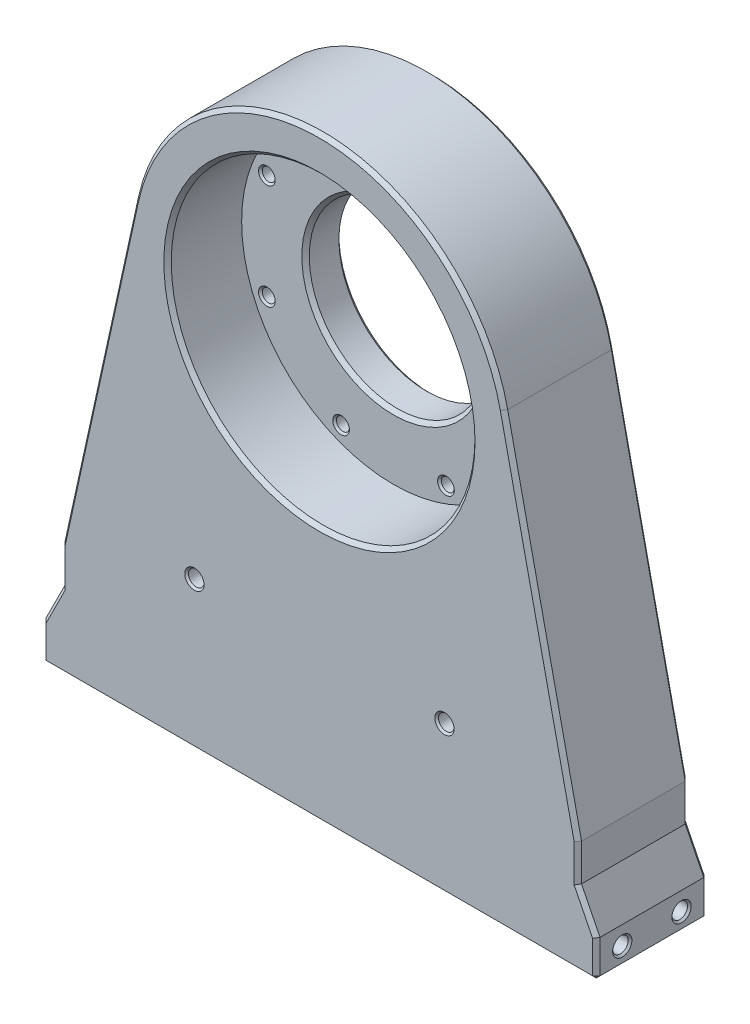
SolidWorks part; units mm, degrees
ref_plane "前视基准面" through (0, 0, 0) normal (0, 0, 1) x (1, 0, 0)
ref_plane "上视基准面" through (0, 0, 0) normal (0, 1, 0) x (1, 0, 0)
ref_plane "右视基准面" through (0, 0, 0) normal (1, 0, 0) x (0, 0, -1)
sketch "草图1" plane through (0, 0, 0) normal (0, 0, 1) x (1, 0, 0)
  line L1 (-74.75, 82.5) -> (74.75, 82.5)
  line L2 (-74.75, 82.5) -> (-74.75, -82.5)
  line L3 (-74.75, -82.5) -> (74.75, -82.5)
  line L4 (74.75, 82.5) -> (74.75, -82.5)
  line L5 (-74.75, 82.5) -> (74.75, -82.5) construction
  line L6 (-74.75, -82.5) -> (74.75, 82.5) construction
  point P0 (0, 0)
  dimension "D1" = 165
  dimension "D2" = 149.5
extrude "凸台-拉伸1" add sketch "草图1" along normal blind 30
sketch "草图2" plane through (0, 0, 30) normal (0, 0, 1) x (1, 0, 0)
  line L0 (-74.75, 82.5) -> (-74.75, -72.5)
  line L1 (-74.75, 82.5) -> (-74.75, -82.5) construction
  line L2 (-74.75, -72.5) -> (-69.75, -62.5)
  line L3 (-69.75, -62.5) -> (-69.75, 82.5)
  line L4 (74.75, 82.5) -> (-74.75, 82.5) construction
  line L5 (-69.75, 82.5) -> (-74.75, 82.5)
  line L6 (0, 82.5) -> (0, -82.5) construction
  line L7 (-74.75, -82.5) -> (74.75, -82.5) construction
  line L8 (69.75, 82.5) -> (74.75, 82.5)
  line L9 (69.75, -62.5) -> (69.75, 82.5)
  line L10 (74.75, -72.5) -> (69.75, -62.5)
  line L11 (74.75, 82.5) -> (74.75, -72.5)
  dimension "D1" = 5
  dimension "D2" = 10
  dimension "D3" = 10
extrude "切除-拉伸1" cut sketch "草图2" against normal through all
sketch "草图3" plane through (0, 0, 30) normal (0, 0, 1) x (1, 0, 0)
  line L0 (0, 82.5) -> (0, -82.5) construction
  line L1 (69.75, 82.5) -> (-69.75, 82.5) construction
  line L2 (-74.75, -82.5) -> (74.75, -82.5) construction
  circle A0 centre (0, 27.5) radius 41
  dimension "D1" = 82
  dimension "D2" = 55
extrude "切除-拉伸2" cut sketch "草图3" against normal offset from surface (20 mm away) 10 up to face at (0, -33.75, 0)
sketch "草图4" plane through (0, 0, 10) normal (0, 0, 1) x (1, 0, 0)
  circle A0 centre (0, 27.5) radius 23.75
  dimension "D1" = 47.5
extrude "切除-拉伸3" cut sketch "草图4" against normal through all
sketch "草图5" plane through (0, 0, 0) normal (0, 0, -1) x (-1, 0, 0)
  line L0 (0, 64.5) -> (0, 27.5) construction
  line L1 (0, 27.5) -> (14.1593, 61.6835) construction
  circle A0 centre (0, 27.5) radius 37 construction
  circle A1 centre (14.1593, 61.6835) radius 1.75
  circle A2 centre (34.1835, 41.6593) radius 1.75
  circle A3 centre (34.1835, 13.3407) radius 1.75
  circle A4 centre (14.1593, -6.6835) radius 1.75
  circle A5 centre (-14.1593, -6.6835) radius 1.75
  circle A6 centre (-34.1835, 13.3407) radius 1.75
  circle A7 centre (-34.1835, 41.6593) radius 1.75
  circle A8 centre (-14.1593, 61.6835) radius 1.75
  point P22 (0, 27.5)
  dimension "D1" = 74
  dimension "D2" = 3.5
  dimension "D4" = 22.5
  dimension "D3" = 8
extrude "切除-拉伸4" cut sketch "草图5" against normal through all
sketch "草图6" plane through (0, 0, 0) normal (0, 0, -1) x (-1, 0, 0)
  circle A0 centre (14.1593, 61.6835) radius 3.1
  circle A1 centre (34.1835, 41.6593) radius 3.1
  circle A2 centre (34.1835, 13.3407) radius 3.1
  circle A3 centre (14.1593, -6.6835) radius 3.1
  circle A4 centre (-14.1593, -6.6835) radius 3.1
  circle A5 centre (-34.1835, 13.3407) radius 3.1
  circle A6 centre (-34.1835, 41.6593) radius 3.1
  circle A7 centre (-14.1593, 61.6835) radius 3.1
  dimension "D1" = 6.2
extrude "切除-拉伸5" cut sketch "草图6" against normal offset from surface (4 mm away) 6 up to face at (-32.4335, 41.6593, 10)
sketch "草图7" plane through (74.75, 0, 0) normal (1, 0, 0) x (0, 0, -1)
  line L0 (-30, -77.5) -> (0, -77.5) construction
  line L1 (-30, -82.5) -> (-30, -72.5) construction
  line L2 (0, -82.5) -> (0, -72.5) construction
  line L3 (-15, -72.5) -> (-15, -82.5) construction
  line L4 (0, -72.5) -> (-30, -72.5) construction
  line L5 (-30, -82.5) -> (0, -82.5) construction
  circle A0 centre (-23, -77.5) radius 2.1
  circle A1 centre (-7, -77.5) radius 2.1
  dimension "D1" = 4.2
  dimension "D2" = 8
extrude "切除-拉伸6" cut sketch "草图7" against normal blind 8
mirror "镜向1" about plane through (0, 0, 0) normal (1, 0, 0) of "切除-拉伸6"
chamfer "倒角1" distance 0.5 angle 45 4 edges at (74.75, -79.6, 7) (74.75, -75.4, 23) (-74.75, -79.6, 7) (-74.75, -75.4, 23)
chamfer "倒角2" distance 1 angle 45 3 edges at (23.75, 27.5, 0) (23.75, 27.5, 10) (41, 27.5, 30)
chamfer "倒角3" distance 0.5 angle 45 24 edges at (-32.4335, 13.3407, 10) (-32.4335, 13.3407, 4) (-12.4093, -6.6835, 10) (-12.4093, -6.6835, 4) (15.9093, -6.6835, 10) (15.9093, -6.6835, 4) (35.9335, 13.3407, 10) (35.9335, 13.3407, 4) (35.9335, 41.6593, 10) (35.9335, 41.6593, 4) (-32.4335, 41.6593, 10) (-32.4335, 41.6593, 4) (-12.4093, 61.6835, 10) (-12.4093, 61.6835, 4) (15.9093, 61.6835, 10) (15.9093, 61.6835, 4) (-37.2835, 41.6593, 0) (-17.2593, 61.6835, 0) (11.0593, 61.6835, 0) (31.0835, 41.6593, 0) (31.0835, 13.3407, 0) (11.0593, -6.6835, 0) (-17.2593, -6.6835, 0) (-37.2835, 13.3407, 0)
sketch "草图8" plane through (0, 0, 30) normal (0, 0, 1) x (1, 0, 0)
  line L0 (-69.75, -52.5) -> (-49.8169, 38.4216)
  line L1 (-69.75, -62.5) -> (-69.75, 82.5) construction
  line L2 (-69.75, -52.5) -> (-69.75, 82.5)
  line L3 (-69.75, 82.5) -> (69.75, 82.5)
  line L4 (69.75, 82.5) -> (-69.75, 82.5) construction
  line L5 (0, 82.5) -> (0, -82.5) construction
  line L6 (-74.75, -82.5) -> (74.75, -82.5) construction
  line L7 (69.75, -52.5) -> (69.75, 82.5)
  line L8 (69.75, -52.5) -> (49.8169, 38.4216)
  arc A0 (49.8169, 38.4216) -> (-49.8169, 38.4216) centre (0, 27.5) ccw
  circle A1 centre (0, 27.5) radius 41 construction
  dimension "D1" = 10
  dimension "D2" = 10
extrude "切除-拉伸7" cut sketch "草图8" against normal through all
chamfer "倒角4" distance 1 angle 45 22 edges at (59.7834, -7.0392, 30) (59.7834, -7.0392, 0) (0, 78.5, 30) (0, 78.5, 0) (69.75, -57.5, 30) (72.25, -67.5, 30) (-59.7834, -7.0392, 30) (-69.75, -57.5, 30) (-72.25, -67.5, 30) (-74.75, -77.5, 30) (0, -82.5, 30) (74.75, -77.5, 30) (74.75, -82.5, 15) (69.75, -57.5, 0) (72.25, -67.5, 0) (74.75, -77.5, 0) (-59.7834, -7.0392, 0) (-69.75, -57.5, 0) (-72.25, -67.5, 0) (-74.75, -77.5, 0) (0, -82.5, 0) (-74.75, -82.5, 15)
sketch "草图9" plane through (0, 0, 30) normal (0, 0, -1) x (-1, 0, 0)
  line L0 (0, 0) -> (0, -81.5) construction
  line L1 (-73.75, -81.5) -> (73.75, -81.5) construction
  line L2 (-33.75, -42.5) -> (33.75, -42.5) construction
  line L3 (73.75, -82.5) -> (-73.75, -82.5) construction
  line L5 (-40, -22.5) -> (40, -22.5) construction
  line L6 (-40, -22.5) -> (-40, -62.5) construction
  line L7 (-40, -62.5) -> (40, -62.5) construction
  line L8 (40, -22.5) -> (40, -62.5) construction
  line L9 (-40, -22.5) -> (40, -62.5) construction
  line L10 (-40, -62.5) -> (40, -22.5) construction
  circle A0 centre (-33.75, -42.5) radius 2.1
  circle A1 centre (33.75, -42.5) radius 2.1
  point P8 (0, -42.5)
  point P12 (0, -42.5)
  dimension "D2" = 4.2
  dimension "D1" = 67.5
  dimension "D3" = 40
  dimension "D4" = 80
  dimension "D5" = 40
extrude "切除-拉伸8" cut sketch "草图9" along normal blind 8
chamfer "倒角5" distance 0.5 angle 45 2 edges at (31.65, -42.5, 30) (-35.85, -42.5, 30)
